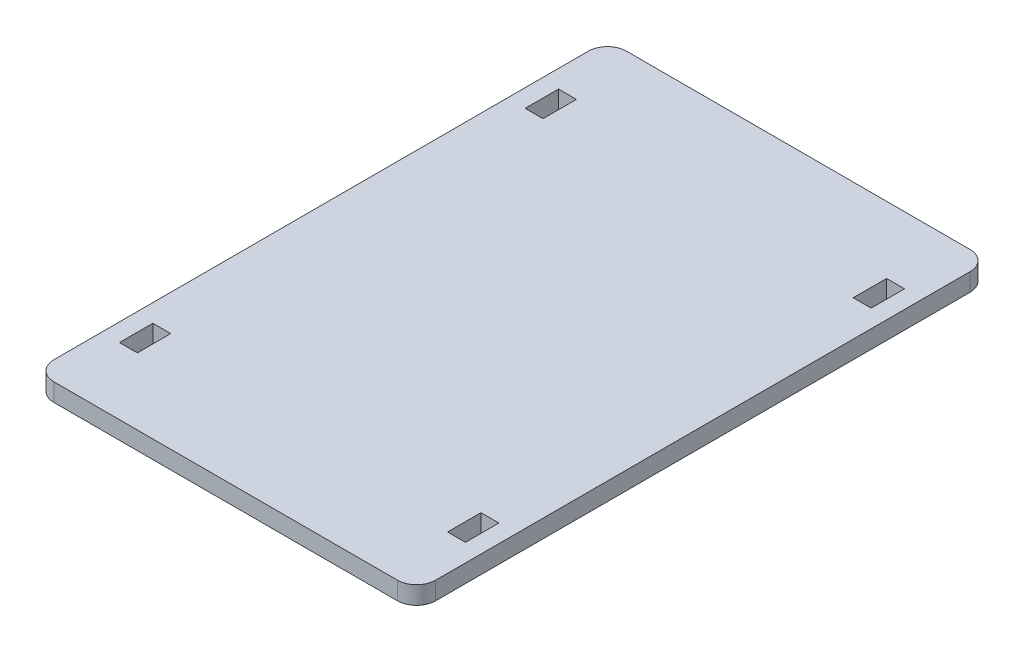
SolidWorks part; units mm, degrees
ref_plane "Front Plane" through (0, 0, 0) normal (0, 0, 1) x (1, 0, 0)
ref_plane "Top Plane" through (0, 0, 0) normal (0, 1, 0) x (1, 0, 0)
ref_plane "Right Plane" through (0, 0, 0) normal (1, 0, 0) x (0, 0, -1)
sketch "Sketch1" plane through (0, 0, 0) normal (0, 1, 0) x (1, 0, 0)
  line L1 (0, 0) -> (-101.6, 0)
  line L2 (0, 0) -> (0, 152.4)
  line L3 (0, 152.4) -> (-101.6, 152.4)
  line L4 (-101.6, 0) -> (-101.6, 152.4)
  dimension "D1" = 101.6
  dimension "D2" = 152.4
extrude "Boss-Extrude1" add sketch "Sketch1" along normal blind 4.7625 contours L3 L4 L1 L2
sketch "Sketch2" plane through (0, 4.7625, 0) normal (0, 1, 0) x (1, 0, 0)
  line L0 (0, -2.6194) -> (0, 2.6194) construction
  line L1 (-4.7625, 134.62) -> (-9.525, 134.62)
  line L2 (-4.7625, 134.62) -> (-4.7625, 125.73)
  line L3 (-4.7625, 125.73) -> (-9.525, 125.73)
  line L4 (-9.525, 134.62) -> (-9.525, 125.73)
  line L5 (0, 152.4) -> (-101.6, 152.4) construction
  line L6 (-50.8, 152.4) -> (-50.8, 128.9502) construction
  line L7 (-101.6, 76.2) -> (-81.2801, 76.2) construction
  line L8 (-101.6, 0) -> (-101.6, 152.4) construction
  line L9 (-96.8375, 125.73) -> (-92.075, 125.73)
  line L10 (-92.075, 134.62) -> (-92.075, 125.73)
  line L11 (-96.8375, 134.62) -> (-92.075, 134.62)
  line L12 (-96.8375, 134.62) -> (-96.8375, 125.73)
  line L13 (-4.7625, 26.67) -> (-9.525, 26.67)
  line L14 (-9.525, 17.78) -> (-9.525, 26.67)
  line L15 (-4.7625, 17.78) -> (-9.525, 17.78)
  line L16 (-4.7625, 17.78) -> (-4.7625, 26.67)
  line L17 (-96.8375, 17.78) -> (-96.8375, 26.67)
  line L18 (-96.8375, 17.78) -> (-92.075, 17.78)
  line L19 (-92.075, 17.78) -> (-92.075, 26.67)
  line L20 (-96.8375, 26.67) -> (-92.075, 26.67)
  dimension "D1" = 4.7625
  dimension "D2" = 8.89
  dimension "D3" = 4.7625
  dimension "D4" = 17.78
extrude "Cut-Extrude1" cut sketch "Sketch2" against normal blind 6.35
fillet "Fillet1" radius 5.08 4 edges at (-101.6, 2.3813, 0) (-101.6, 2.3813, -152.4) (0, 2.3813, -152.4) (0, 2.3813, 0)
